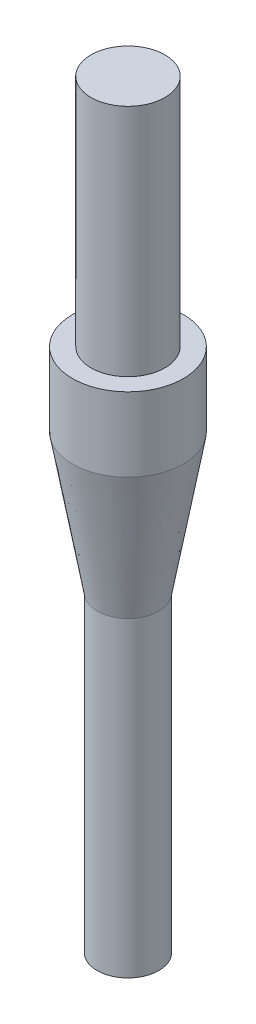
SolidWorks part; units mm, degrees
ref_plane "Спереди" through (0, 0, 0) normal (0, 0, 1) x (1, 0, 0)
ref_plane "Сверху" through (0, 0, 0) normal (0, 1, 0) x (1, 0, 0)
ref_plane "Справа" through (0, 0, 0) normal (1, 0, 0) x (0, 0, -1)
sketch "Эскиз1" plane through (0, 0, -5.8) normal (0, 0, -1) x (-1, 0, 0)
  line L0 (-15.9749, 44) -> (-19.2249, 44) construction
  line L1 (-15.9749, 44) -> (-19.2249, 44) construction
  line L2 (-16.0999, 15.7012) -> (-19.0999, 15.7012) construction
  line L3 (-16.0999, 15.7012) -> (-19.0999, 15.7012) construction
  line L4 (-16.0999, 23.1) -> (-19.0999, 23.1) construction
  line L5 (-16.0999, 23.1) -> (-19.0999, 23.1) construction
  line L6 (-19.2249, 37.5) -> (-15.9749, 37.5) construction
  line L7 (-19.2249, 37.5) -> (-15.9749, 37.5) construction
  line L8 (-17.5999, 51.6965) -> (-17.5999, -5.4965) construction
  line L9 (-17.5999, 47) -> (-19.0999, 47)
  line L10 (-19.0999, 47) -> (-19.0999, 37.5)
  line L11 (-19.0999, 37.5) -> (-19.8499, 37.5)
  line L12 (-19.8499, 37.5) -> (-19.8499, 34.5)
  line L13 (-19.8499, 34.5) -> (-18.8499, 28.8287)
  line L14 (-18.8499, 28.8287) -> (-18.8499, 16.2012)
  line L15 (-18.8499, 16.2012) -> (-17.5999, 16.2012)
  line L16 (-17.5999, 47) -> (-17.5999, 16.2012)
  point P10 (-17.5999, 23.1)
  dimension "D1" = 1.5
  dimension "D2" = 3
  dimension "D3" = 0.75
  dimension "D4" = 170
  dimension "D5" = 1.25
  dimension "D6" = 0.5
  dimension "D7" = 3
revolve "Повернуть1" add sketch "Эскиз1" angle 360 about L16
